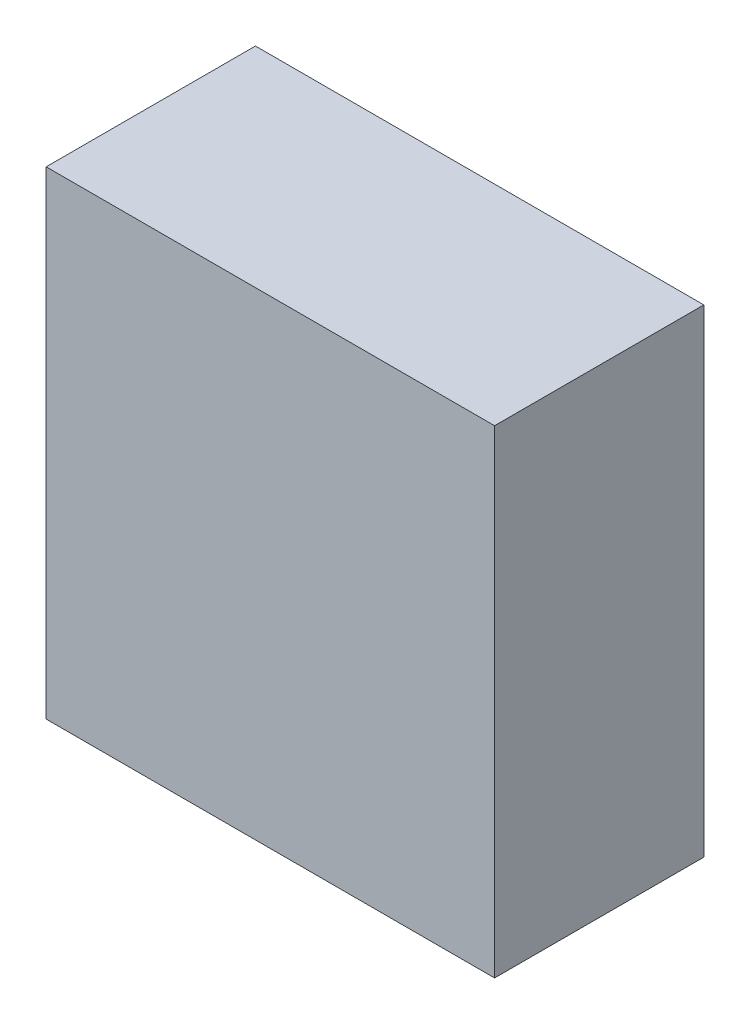
SolidWorks part; units mm, degrees
ref_plane "Front Plane" through (0, 0, 0) normal (0, 0, 1) x (1, 0, 0)
ref_plane "Top Plane" through (0, 0, 0) normal (0, 1, 0) x (1, 0, 0)
ref_plane "Right Plane" through (0, 0, 0) normal (1, 0, 0) x (0, 0, -1)
sketch "Sketch1" plane through (0, 0, 0) normal (0, 0, 1) x (1, 0, 0)
  line L1 (0, 0) -> (-30, 0)
  line L2 (0, 0) -> (0, 32)
  line L3 (0, 32) -> (-30, 32)
  line L4 (-30, 0) -> (-30, 32)
  dimension "D1" = 30
  dimension "D2" = 32
extrude "Boss-Extrude1" add sketch "Sketch1" along normal blind 14
